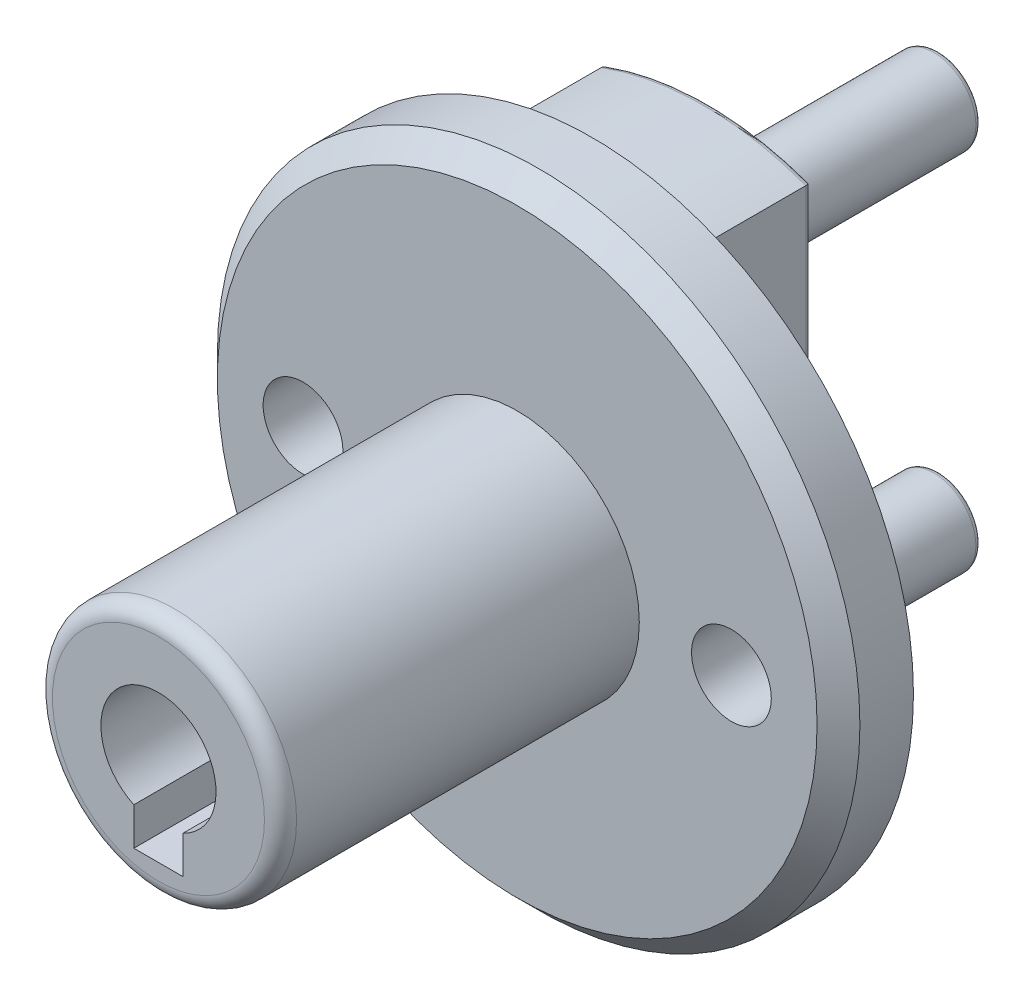
SolidWorks part; units mm, degrees
material "Custom Plastic"
ref_plane "X-Y Datum" through (0, 0, 0) normal (0, 0, 1) x (1, 0, 0)
ref_plane "X-Z Datum" through (0, 0, 0) normal (0, 1, 0) x (1, 0, 0)
ref_plane "Y-Z Datum" through (0, 0, 0) normal (1, 0, 0) x (0, 0, -1)
sketch "Sketch2" plane through (0, 0, 0) normal (0, 0, 1) x (1, 0, 0)
  circle A0 centre (0, 0) radius 30
  dimension "D1" = 60
extrude "Boss-Extrude1" add sketch "Sketch2" along normal blind 7
sketch "Sketch3" plane through (0, 0, 7) normal (0, 0, 1) x (1, 0, 0)
  circle A0 centre (0, 0) radius 11.4
  dimension "D1" = 22.8
extrude "Boss-Extrude2" add sketch "Sketch3" along normal blind 33.5
sketch "Sketch4" plane through (0, 0, 0) normal (0, 0, -1) x (-1, 0, 0)
  line L1 (-9.55, 25.6819) -> (9.55, 25.6819)
  line L2 (-9.55, 25.6819) -> (-9.55, -25.6819)
  line L3 (-9.55, -25.6819) -> (9.55, -25.6819)
  line L4 (9.55, 25.6819) -> (9.55, -25.6819)
  line L5 (-9.55, 25.6819) -> (9.55, -25.6819) construction
  line L6 (-9.55, -25.6819) -> (9.55, 25.6819) construction
  circle A0 centre (0, 0) radius 11.45
  circle A1 centre (0, 0) radius 27.4
  point P0 (0, 0)
  point P9 (-9.55, 25.6819)
  dimension "D2" = 22.9
  dimension "D3" = 54.8
  dimension "D1" = 19.1
extrude "Boss-Extrude3" add sketch "Sketch4" along normal blind 10.9 contours L2 A0 | L4 A0 | L4 A0 L2 | A0 L2 L3 L4 | A0 L4 L1 L2 | L1 A1 | L3 A1
sketch "Sketch5" plane through (0, 0, -10.9) normal (0, 0, -1) x (-1, 0, 0)
  circle A0 centre (0, 0) radius 6.5
  dimension "D1" = 13
extrude "Boss-Extrude4" add sketch "Sketch5" along normal blind 3
sketch "Sketch6" plane through (0, 0, -10.9) normal (0, 0, -1) x (-1, 0, 0)
  line L0 (0, 17) -> (0, -17) construction
  circle A0 centre (0, -17) radius 3.925
  circle A1 centre (0, 17) radius 3.925
  point P5 (0, 0)
  dimension "D2" = 7.85
  dimension "D1" = 34
extrude "Boss-Extrude5" add sketch "Sketch6" along normal blind 21.5
sketch "Sketch7" plane through (0, 0, 7) normal (0, 0, 1) x (1, 0, 0)
  line L0 (20, 0) -> (-20, 0) construction
  circle A0 centre (20, 0) radius 3.725
  circle A1 centre (-20, 0) radius 3.725
  point P5 (0, 0)
  dimension "D1" = 7.45
  dimension "D2" = 40
extrude "Cut-Extrude1" cut sketch "Sketch7" against normal through all
sketch "Sketch8" plane through (0, 0, 40.5) normal (0, 0, 1) x (1, 0, 0)
  line L1 (-2.3, -2.375) -> (2.3, -2.375)
  line L2 (-2.3, -2.375) -> (-2.3, -8.375)
  line L3 (-2.3, -8.375) -> (2.3, -8.375)
  line L4 (2.3, -2.375) -> (2.3, -8.375)
  line L5 (-2.3, -2.375) -> (2.3, -8.375) construction
  line L6 (-2.3, -8.375) -> (2.3, -2.375) construction
  circle A0 centre (0, 0) radius 5.375
  point P3 (0, -5.375)
  dimension "D1" = 10.75
  dimension "D2" = 4.6
  dimension "D3" = 6
extrude "Cut-Extrude2" cut sketch "Sketch8" against normal blind 16.5 contours L4 A0 L2 L1 | L2 A0 L4 L1 | A0 L2 L3 L4
chamfer "Chamfer1" distance 2 angle 45 1 edges at (30, 0, 7)
fillet "Fillet1" radius 1.5 1 edges at (11.4, 0, 40.5)
fillet "Fillet2" radius 0.5 22 edges at (-6.5, 0, -13.9) (-3.925, 17, -32.4) (-3.925, -17, -32.4) (9.55, -15.9992, 0) (9.55, -15.9992, -10.9) (9.55, 15.9992, 0) (9.55, 15.9992, -10.9) (0, -27.4, 0) (0, -27.4, -10.9) (0, 27.4, 0) (0, 27.4, -10.9) (-9.55, -15.9992, 0) (-9.55, -15.9992, -10.9) (-9.55, 15.9992, 0) (-9.55, 15.9992, -10.9) (-11.45, 0, 0) (-11.45, 0, -10.9) (11.45, 0, 0) (11.45, 0, -10.9) (-6.5, 0, -10.9) (-3.925, -17, -10.9) (-3.925, 17, -10.9)
